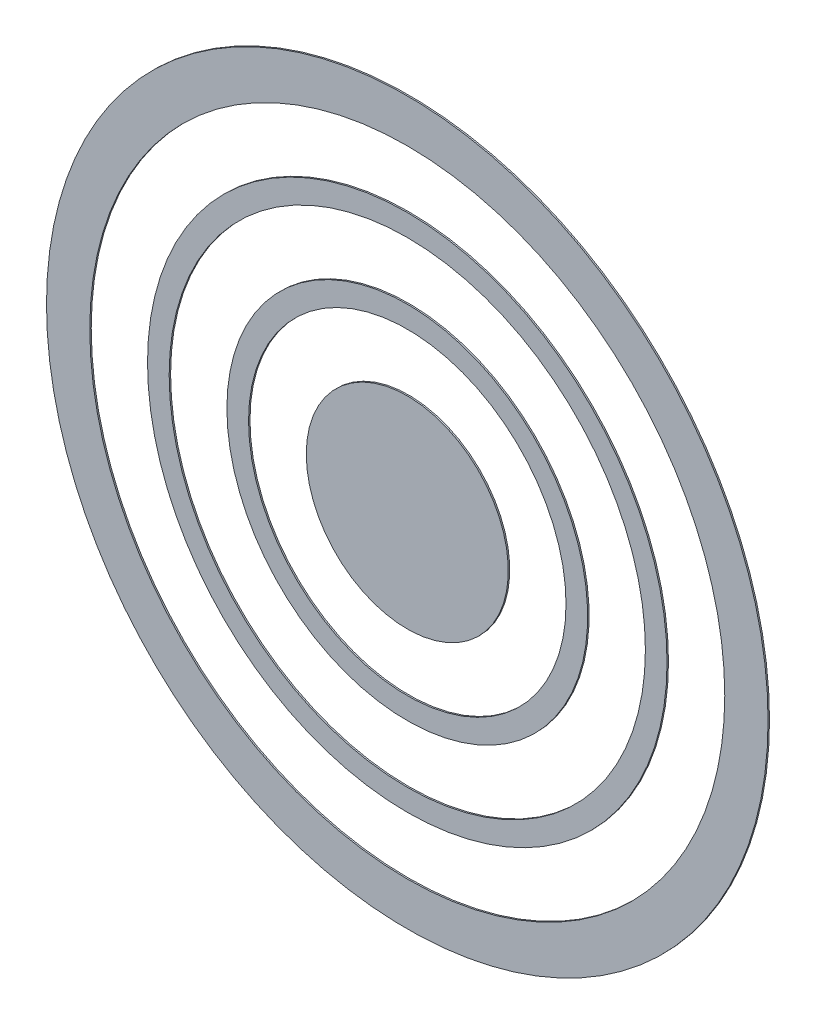
SolidWorks part; units mm, degrees
material "ABS"
ref_plane "Front" through (0, 0, 0) normal (0, 0, 1) x (1, 0, 0)
ref_plane "Top" through (0, 0, 0) normal (0, 1, 0) x (1, 0, 0)
ref_plane "Right" through (0, 0, 0) normal (1, 0, 0) x (0, 0, -1)
sketch "Эскиз1" plane through (0, 0, 0) normal (0, 0, 1) x (1, 0, 0)
  line L0 (0, 0.7) -> (0, 1.1) construction
  line L1 (0, 1.25) -> (0, 1.65) construction
  line L2 (0, 1.8) -> (0, 2.2) construction
  circle A0 centre (0, 0) radius 2.5
  circle A1 centre (0, 0) radius 2.2
  circle A2 centre (0, 0) radius 1.8
  circle A3 centre (0, 0) radius 1.65
  circle A4 centre (0, 0) radius 0.7
  circle A5 centre (0, 0) radius 1.1
  circle A6 centre (0, 0) radius 1.25
  dimension "D1" = 5
  dimension "D2" = 0.3
  dimension "D3" = 0.15
  dimension "D4" = 1.4
  dimension "D6" = 0.15
extrude "Бобышка-Вытянуть1" add sketch "Эскиз1" along normal blind 0.01 contours A0 A1 | A2 A3 | A6 A5 | A4
